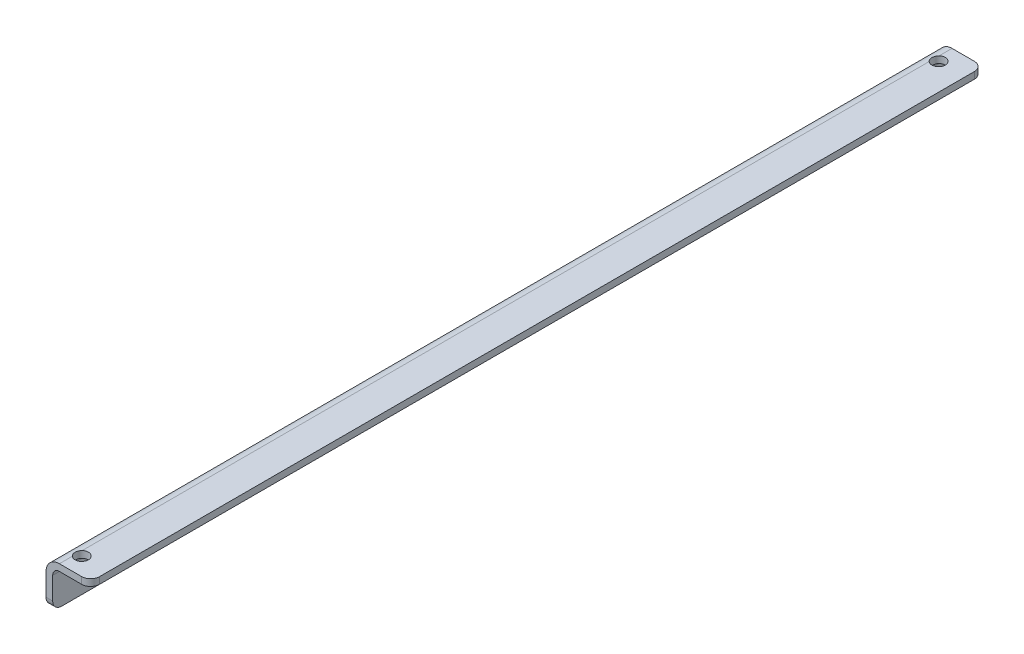
SolidWorks part; units mm, degrees
ref_plane "Спереди" through (0, 0, 0) normal (0, 0, 1) x (1, 0, 0)
ref_plane "Сверху" through (0, 0, 0) normal (0, 1, 0) x (1, 0, 0)
ref_plane "Справа" through (0, 0, 0) normal (1, 0, 0) x (0, 0, -1)
sketch "Эскиз1" plane through (0, 0, 0) normal (0, 0, 1) x (1, 0, 0)
  line L1 (0, 0) -> (1.5, 0)
  line L2 (0, 0) -> (0, 7)
  line L3 (3, 10) -> (10, 10)
  line L4 (10, 8.5) -> (10, 10)
  line L6 (1.5, 0) -> (1.5, 7)
  line L7 (3, 8.5) -> (10, 8.5)
  arc A0 (0, 7) -> (3, 10) centre (3, 7) cw
  arc A1 (3, 8.5) -> (1.5, 7) centre (3, 7) ccw
  point P8 (0, 10)
  dimension "D5" = 3
  dimension "D6" = 3
  dimension "D1" = 10
  dimension "D2" = 10
  dimension "D3" = 1.5
  dimension "D4" = 1.5
extrude "Вытянуть1" add sketch "Эскиз1" along normal blind 200
sketch "Эскиз2" plane through (0, 10, 0) normal (0, 1, 0) x (-1, 0, 0)
  line L0 (-4, 405.0815) -> (-4, 316.8769) construction
  line L1 (-10, 200) -> (-10, 0) construction
  line L2 (-10, 200) -> (-3, 200) construction
  line L3 (-59.6379, 100) -> (66.3243, 100) construction
  line L5 (-10, 0) -> (-3, 0) construction
  circle A0 centre (-4, 196) radius 1.5
  circle A1 centre (-4, 4) radius 1.5
  circle A4 centre (-4, -88) radius 0.95
  dimension "D5" = 3
  dimension "D6" = 3
  dimension "D9" = 92
  dimension "D1" = 6
  dimension "D2" = 4
extrude "Вырез-Вытянуть1" cut sketch "Эскиз2" against normal blind 5
fillet "Скругление1" radius 2 4 edges at (0.75, 0, 0) (10, 9.25, 0) (10, 9.25, 200) (0.75, 0, 200)
